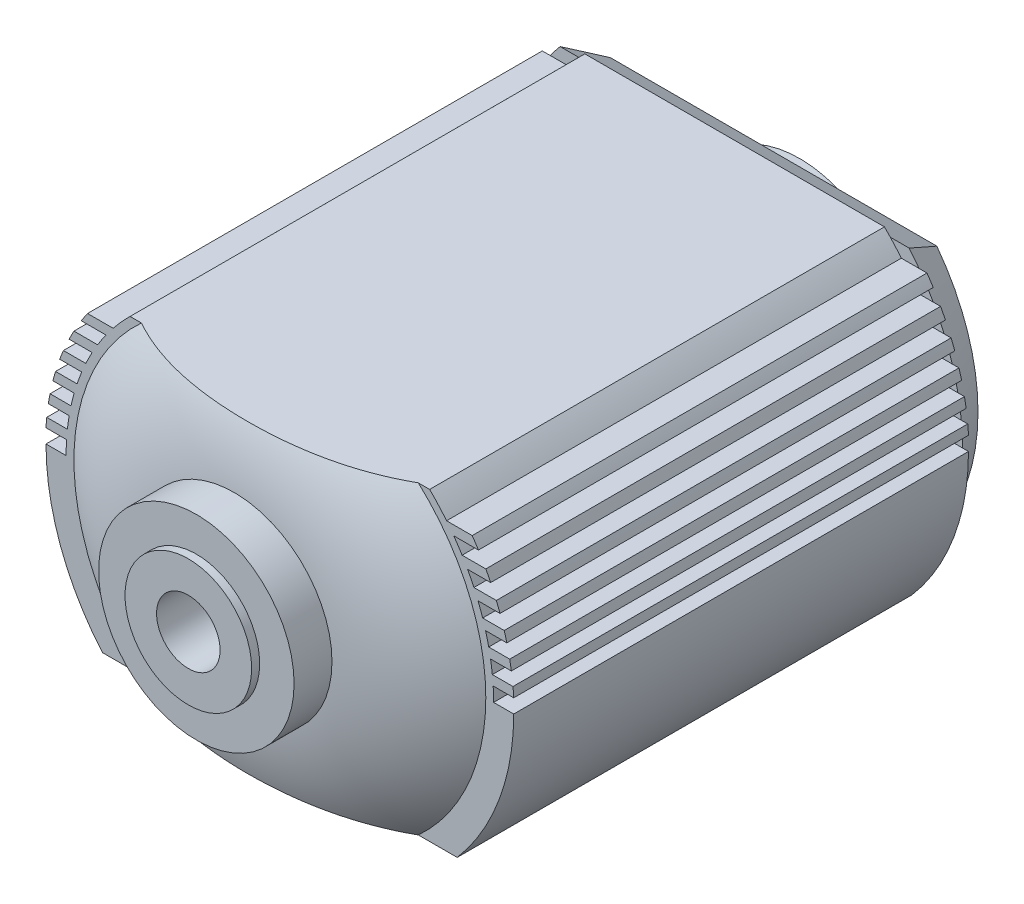
SolidWorks part; units mm, degrees
ref_plane "Plan de face" through (0, 0, 0) normal (0, 0, 1) x (1, 0, 0)
ref_plane "Plan de dessus" through (0, 0, 0) normal (0, 1, 0) x (1, 0, 0)
ref_plane "Plan de droite" through (0, 0, 0) normal (1, 0, 0) x (0, 0, -1)
sketch "Esquisse1" plane through (0, 0, 0) normal (0, 0, 1) x (1, 0, 0)
  line L0 (0, -1.1735) -> (0, -3.1095) construction
  line L1 (1.6451, 0) -> (2.6949, 0) construction
  line L2 (1.1529, 1.1735) -> (-1.1529, 1.1735)
  line L3 (-1.1529, 1.1735) -> (1.1529, 1.1735)
  line L4 (-1.369, -1.1735) -> (-1.1529, -1.1735)
  line L5 (0, -1.1735) -> (-1.1529, -1.1735)
  line L6 (1.7999, 0) -> (1.6451, 0)
  line L7 (1.2831, 1.0296) -> (1.4803, 1.0296)
  line L8 (-1.7999, 0) -> (-1.6451, 0)
  line L9 (1.3381, 0.957) -> (1.5283, 0.957)
  line L10 (0, -1.1735) -> (1.1529, -1.1735)
  line L11 (1.4025, 0.8597) -> (1.585, 0.8597)
  line L12 (1.1529, -1.1735) -> (1.3648, -1.1735)
  line L13 (1.4445, 0.7871) -> (1.6223, 0.7871)
  line L14 (-1.6415, 0.1078) -> (-1.7999, 0.1078)
  line L15 (1.4934, 0.6899) -> (1.666, 0.6899)
  line L16 (-1.6351, 0.1804) -> (-1.7941, 0.1804)
  line L17 (1.5249, 0.6173) -> (1.6942, 0.6173)
  line L18 (-1.6215, 0.2777) -> (-1.7817, 0.2777)
  line L19 (1.5607, 0.5201) -> (1.7265, 0.5201)
  line L20 (-1.6073, 0.3503) -> (-1.7688, 0.3503)
  line L21 (1.583, 0.4475) -> (1.7468, 0.4475)
  line L22 (-1.583, 0.4475) -> (-1.7468, 0.4475)
  line L23 (1.6073, 0.3503) -> (1.7688, 0.3503)
  line L24 (-1.5607, 0.5201) -> (-1.7265, 0.5201)
  line L25 (1.6215, 0.2777) -> (1.7817, 0.2777)
  line L26 (-1.5249, 0.6173) -> (-1.6942, 0.6173)
  line L27 (1.6351, 0.1804) -> (1.7941, 0.1804)
  line L28 (-1.4934, 0.6899) -> (-1.666, 0.6899)
  line L29 (1.6415, 0.1078) -> (1.7999, 0.1078)
  line L30 (1.5064, 0.1804) -> (1.5064, 0.1078) [skipped]
  line L31 (1.4468, 0.3503) -> (1.4468, 0.2777) [skipped]
  line L32 (1.2678, 0.8597) -> (1.2678, 0.7871) [skipped]
  line L33 (1.2081, 1.0296) -> (1.2081, 0.957) [skipped]
  line L34 (1.3274, 0.6899) -> (1.3274, 0.6173) [skipped]
  line L35 (1.3871, 0.5201) -> (1.3871, 0.4475) [skipped]
  line L36 (1.7003, 1.0296) -> (1.7003, 0.957) [skipped]
  line L37 (1.76, 0.8597) -> (1.76, 0.7871) [skipped]
  line L38 (1.8196, 0.6899) -> (1.8196, 0.6173) [skipped]
  line L39 (1.8793, 0.5201) -> (1.8793, 0.4475) [skipped]
  line L40 (1.939, 0.3503) -> (1.939, 0.2777) [skipped]
  line L41 (1.9986, 0.1804) -> (1.9986, 0.1078) [skipped]
  line L42 (-1.4445, 0.7871) -> (-1.6223, 0.7871)
  line L43 (-1.4025, 0.8597) -> (-1.585, 0.8597)
  line L44 (-1.3381, 0.957) -> (-1.5283, 0.957)
  line L45 (-1.2831, 1.0296) -> (-1.4803, 1.0296)
  arc A0 (1.7999, 0) -> (1.3648, -1.1735) centre (0, 0) cw
  arc A1 (-1.3648, -1.1735) -> (-1.7999, 0) centre (0, 0) cw
  arc A2 (-1.1529, 1.1735) -> (-1.2831, 1.0296) centre (0, 0) ccw
  arc A3 (1.5283, 0.957) -> (1.4803, 1.0296) centre (0, 0) ccw
  arc A4 (1.6451, 0) -> (1.6415, 0.1078) centre (0, 0) ccw
  arc A5 (1.6223, 0.7871) -> (1.585, 0.8597) centre (0, 0) ccw
  arc A6 (1.6942, 0.6173) -> (1.666, 0.6899) centre (0, 0) ccw
  arc A7 (1.7468, 0.4475) -> (1.7265, 0.5201) centre (0, 0) ccw
  arc A8 (1.7817, 0.2777) -> (1.7688, 0.3503) centre (0, 0) ccw
  arc A9 (1.7999, 0.1078) -> (1.7941, 0.1804) centre (0, 0) ccw
  arc A10 (1.2831, 1.0296) -> (1.1529, 1.1735) centre (0, 0) ccw
  arc A11 (1.4025, 0.8597) -> (1.3381, 0.957) centre (0, 0) ccw
  arc A12 (1.4934, 0.6899) -> (1.4445, 0.7871) centre (0, 0) ccw
  arc A13 (1.5607, 0.5201) -> (1.5249, 0.6173) centre (0, 0) ccw
  arc A14 (-1.1529, 1.1735) -> (-1.2831, 1.0296) centre (0, 0) ccw
  arc A15 (1.6451, 0) -> (1.6415, 0.1078) centre (0, 0) ccw
  arc A16 (1.4025, 0.8597) -> (1.3381, 0.957) centre (0, 0) ccw
  arc A17 (1.2831, 1.0296) -> (1.1529, 1.1735) centre (0, 0) ccw
  arc A18 (1.4934, 0.6899) -> (1.4445, 0.7871) centre (0, 0) ccw
  arc A19 (1.5607, 0.5201) -> (1.5249, 0.6173) centre (0, 0) ccw
  arc A20 (1.6073, 0.3503) -> (1.583, 0.4475) centre (0, 0) ccw
  arc A21 (1.6351, 0.1804) -> (1.6215, 0.2777) centre (0, 0) ccw
  arc A22 (-1.6351, 0.1804) -> (-1.6215, 0.2777) centre (0, 0) cw
  arc A23 (-1.6073, 0.3503) -> (-1.583, 0.4475) centre (0, 0) cw
  arc A24 (-1.5607, 0.5201) -> (-1.5249, 0.6173) centre (0, 0) cw
  arc A25 (-1.4934, 0.6899) -> (-1.4445, 0.7871) centre (0, 0) cw
  arc A26 (-1.4025, 0.8597) -> (-1.3381, 0.957) centre (0, 0) cw
  arc A27 (-1.5607, 0.5201) -> (-1.5249, 0.6173) centre (0, 0) cw
  arc A28 (-1.4934, 0.6899) -> (-1.4445, 0.7871) centre (0, 0) cw
  arc A29 (-1.4025, 0.8597) -> (-1.3381, 0.957) centre (0, 0) cw
  arc A30 (-1.7999, 0.1078) -> (-1.7941, 0.1804) centre (0, 0) cw
  arc A31 (-1.7817, 0.2777) -> (-1.7688, 0.3503) centre (0, 0) cw
  arc A32 (-1.7468, 0.4475) -> (-1.7265, 0.5201) centre (0, 0) cw
  arc A33 (-1.6942, 0.6173) -> (-1.666, 0.6899) centre (0, 0) cw
  arc A34 (-1.6223, 0.7871) -> (-1.585, 0.8597) centre (0, 0) cw
  arc A35 (-1.5283, 0.957) -> (-1.4803, 1.0296) centre (0, 0) cw
  arc A36 (-1.3381, 0.957) -> (-1.4025, 0.8597) centre (0, 0) ccw
  arc A37 (-1.4445, 0.7871) -> (-1.4934, 0.6899) centre (0, 0) ccw
  arc A38 (-1.5249, 0.6173) -> (-1.5607, 0.5201) centre (0, 0) ccw
  arc A39 (-1.583, 0.4475) -> (-1.6073, 0.3503) centre (0, 0) ccw
  arc A40 (-1.6215, 0.2777) -> (-1.6351, 0.1804) centre (0, 0) ccw
  arc A41 (-1.6415, 0.1078) -> (-1.6451, 0) centre (0, 0) ccw
  arc A42 (-1.6415, 0.1078) -> (-1.6451, 0) centre (0, 0) ccw
  arc A43 (-1.6215, 0.2777) -> (-1.6351, 0.1804) centre (0, 0) ccw
  arc A44 (-1.583, 0.4475) -> (-1.6073, 0.3503) centre (0, 0) ccw
  arc A45 (-1.5249, 0.6173) -> (-1.5607, 0.5201) centre (0, 0) ccw
  arc A46 (-1.4445, 0.7871) -> (-1.4934, 0.6899) centre (0, 0) ccw
  arc A47 (-1.3381, 0.957) -> (-1.4025, 0.8597) centre (0, 0) ccw
  circle A48 centre (0, 0) radius 1.0815
  dimension "D1" = 6
extrude "Boss.-Extru.1" add sketch "Esquisse1" along normal blind 3.5 contours L14 A41 L8 A1 L4 L5 L10 L12 A0 L6 A4 L29 A9 L27 A21 L25 A8 L23 A20 L21 A7 L19 A13 L17 A6 L15 A12 L13 A5 L11 A11 L9 A3 L7 A10 L2 A2 L45 A35 L44 A26 L43 A34 L42 A25 L28 A33 L26 A24 L24 A32
sketch "Esquisse2" plane through (0, 0, 0) normal (0, 1, 0) x (1, 0, 0)
  line L0 (0, -3.5) -> (0, 0.7223) construction
  line L1 (1.1529, -3.5) -> (-1.1529, -3.5) construction
  line L2 (1.585, -3.5) -> (0.2445, -3.5)
  line L5 (0.4872, -4.1427) -> (0.7522, -4.1427)
  line L6 (0.7522, -3.8512) -> (0.7522, -4.1427)
  line L9 (0.2445, -4.2046) -> (0.4872, -4.2046)
  line L10 (0.4872, -4.1427) -> (0.4872, -4.2046)
  line L14 (0.2445, -4.2046) -> (0.2445, -3.5)
  spline S0 degree 2 poles (0.7522, -3.8512) (1.2205, -3.8032) (1.585, -3.5) knots 0 0 0 1 1 1
revolve "Révolution1" add sketch "Esquisse2" angle 360 about L0
sketch "Esquisse3" plane through (0, 0, 0) normal (0, 0, -1) x (-1, 0, 0)
  line L0 (0, 0) -> (0, -1.7615) construction
  line L1 (0, 0) -> (2.288, 0) construction
  line L2 (-1.3431, 1.1271) -> (1.3431, 1.1271)
  line L5 (-1.3431, -1.1271) -> (1.3431, -1.1271)
  arc A0 (1.3431, -1.1271) -> (1.3431, 1.1271) centre (0, 0) ccw
  arc A1 (-1.3431, -1.1271) -> (-1.3431, 1.1271) centre (0, 0) cw
  circle A2 centre (0, 0) radius 0.4104
  point P9 (0, -1.1271)
  point P10 (0, 1.1271)
extrude "Boss.-Extru.2" add sketch "Esquisse3" along normal blind 0.3 draft 31
sketch "Esquisse4" plane through (0, 0, -0.3) normal (0, 0, -1) x (-1, 0, 0)
  line L1 (-1.1529, 1.1735) -> (1.244, 1.1735)
  line L2 (-1.1529, 1.1735) -> (-1.1529, 1.8077)
  line L3 (-1.1529, 1.8077) -> (1.244, 1.8077)
  line L4 (1.244, 1.1735) -> (1.244, 1.8077)
  line L5 (-1.3648, -1.1735) -> (1.3898, -1.1735)
  line L6 (-1.3648, -1.1735) -> (-1.3648, -1.7494)
  line L7 (-1.3648, -1.7494) -> (1.3898, -1.7494)
  line L8 (1.3898, -1.1735) -> (1.3898, -1.7494)
extrude "Enlèv. mat.-Extru.1" cut sketch "Esquisse4" against normal blind 10.3
sketch "Esquisse5" plane through (0, 0, -0.3) normal (0, 0, -1) x (-1, 0, 0)
  circle A0 centre (0, 0) radius 0.2445
  circle A1 centre (0, 0) radius 0.8032
extrude "Boss.-Extru.3" add sketch "Esquisse5" along normal blind 0.2
